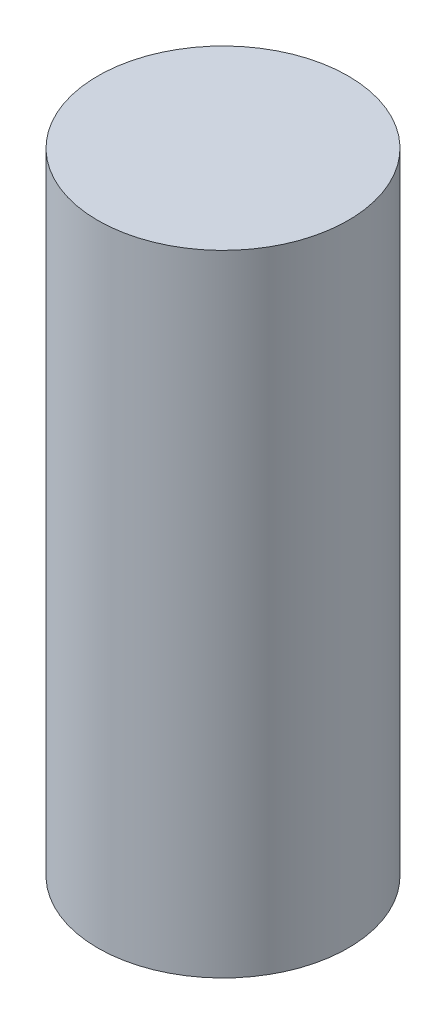
SolidWorks part; units mm, degrees
material "1.4000 (X6Cr13)"
ref_plane "Płaszczyzna przednia" through (0, 0, 0) normal (0, 0, 1) x (1, 0, 0)
ref_plane "Płaszczyzna górna" through (0, 0, 0) normal (0, 1, 0) x (1, 0, 0)
ref_plane "Płaszczyzna prawa" through (0, 0, 0) normal (1, 0, 0) x (0, 0, -1)
sketch "Szkic1" plane through (0, 0, 0) normal (0, 1, 0) x (1, 0, 0)
  circle A0 centre (0, 0) radius 2.225
  dimension "D1" = 4.45
extrude "Dodanie-wyciągnięcie1" add sketch "Szkic1" along normal mid plane 11.2
